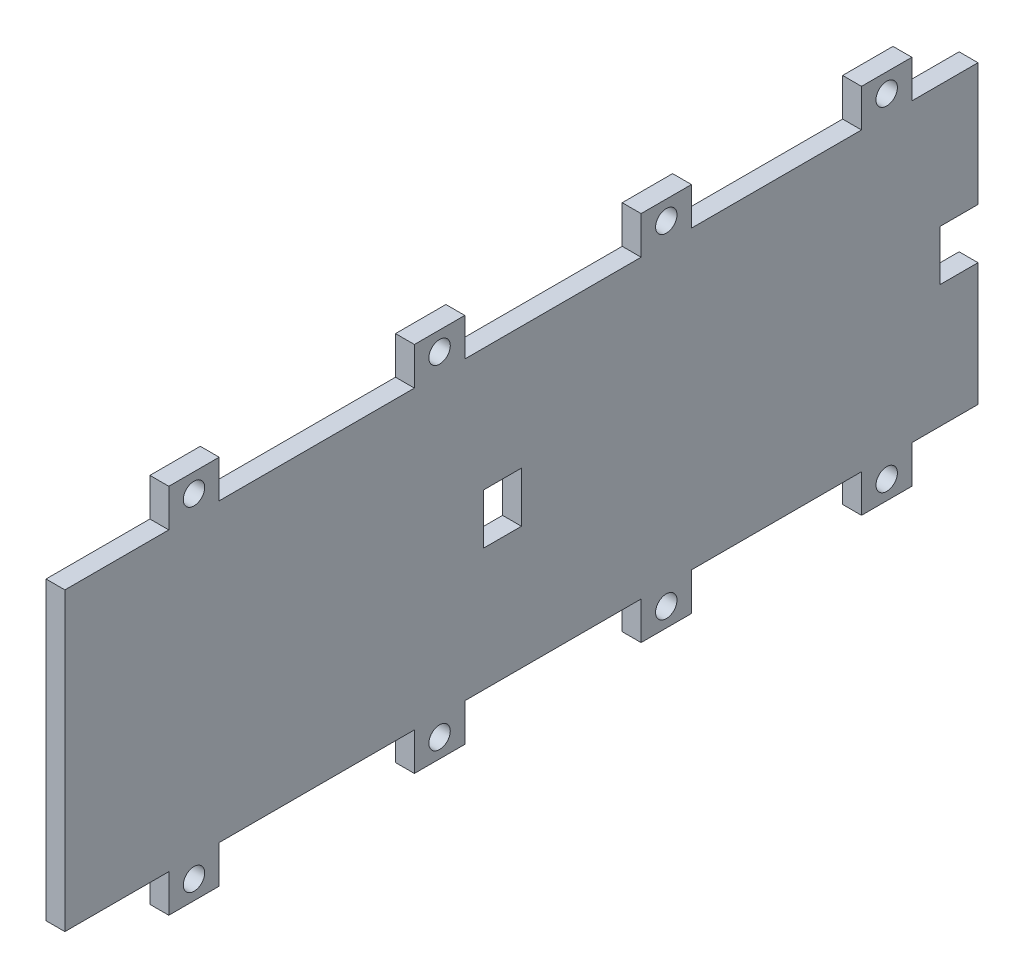
SolidWorks part; units mm, degrees
ref_plane "Front Plane" through (0, 0, 0) normal (0, 0, 1) x (1, 0, 0)
ref_plane "Top Plane" through (0, 0, 0) normal (0, 1, 0) x (1, 0, 0)
ref_plane "Right Plane" through (0, 0, 0) normal (1, 0, 0) x (0, 0, -1)
sketch "草圖1" plane through (0, 0, 0) normal (1, 0, 0) x (0, 0, -1)
  line L0 (-10.5, 23.5) -> (-21, 23.5)
  line L1 (-21, 23.5) -> (-21, 29.5)
  line L2 (-21, 29.5) -> (-29, 29.5)
  line L3 (-29, 29.5) -> (-29, 23.5)
  line L4 (-29, 23.5) -> (-56, 23.5)
  line L5 (-56, 23.5) -> (-56, 29.5)
  line L6 (-56, 29.5) -> (-64, 29.5)
  line L7 (-64, 29.5) -> (-64, 23.5)
  line L8 (-64, 23.5) -> (-92, 23.5)
  line L9 (-92, 23.5) -> (-92, 29.5)
  line L10 (-92, 29.5) -> (-100, 29.5)
  line L11 (-100, 29.5) -> (-100, 23.5)
  line L12 (-100, 23.5) -> (-131, 23.5)
  line L13 (-131, 23.5) -> (-131, 29.5)
  line L14 (-131, 29.5) -> (-139, 29.5)
  line L15 (-139, 29.5) -> (-139, 23.5)
  line L16 (-139, 23.5) -> (-155.5, 23.5)
  line L17 (-155.5, 23.5) -> (-155.5, -23.5)
  line L18 (-155.5, -23.5) -> (-139, -23.5)
  line L19 (-139, -23.5) -> (-139, -29.5)
  line L20 (-139, -29.5) -> (-131, -29.5)
  line L21 (-131, -29.5) -> (-131, -23.5)
  line L22 (-131, -23.5) -> (-100, -23.5)
  line L23 (-100, -23.5) -> (-100, -29.5)
  line L24 (-100, -29.5) -> (-92, -29.5)
  line L25 (-92, -29.5) -> (-92, -23.5)
  line L26 (-92, -23.5) -> (-64, -23.5)
  line L27 (-64, -23.5) -> (-64, -29.5)
  line L28 (-64, -29.5) -> (-56, -29.5)
  line L29 (-56, -29.5) -> (-56, -23.5)
  line L30 (-56, -23.5) -> (-29, -23.5)
  line L31 (-29, -23.5) -> (-29, -29.5)
  line L32 (-29, -29.5) -> (-21, -29.5)
  line L33 (-21, -29.5) -> (-21, -23.5)
  line L34 (-21, -23.5) -> (-10.5, -23.5)
  line L35 (-10.5, -23.5) -> (-10.5, -4)
  line L36 (-10.5, -4) -> (-16.5, -4)
  line L37 (-16.5, -4) -> (-16.5, 4)
  line L38 (-16.5, 4) -> (-10.5, 4)
  line L39 (-10.5, 4) -> (-10.5, 23.5)
  line L40 (-89, -4) -> (-83, -4)
  line L41 (-83, -4) -> (-83, 4)
  line L42 (-83, 4) -> (-89, 4)
  line L43 (-89, 4) -> (-89, -4)
  circle A0 centre (-25, 26.5) radius 1.7
  circle A1 centre (-25, -26.5) radius 1.7
  circle A2 centre (-60, 26.5) radius 1.7
  circle A3 centre (-60, -26.5) radius 1.7
  circle A4 centre (-96, 26.5) radius 1.7
  circle A5 centre (-96, -26.5) radius 1.7
  circle A6 centre (-135, 26.5) radius 1.7
  circle A7 centre (-135, -26.5) radius 1.7
extrude "填料-伸長1" add sketch "草圖1" along normal blind 3 from offset 11
